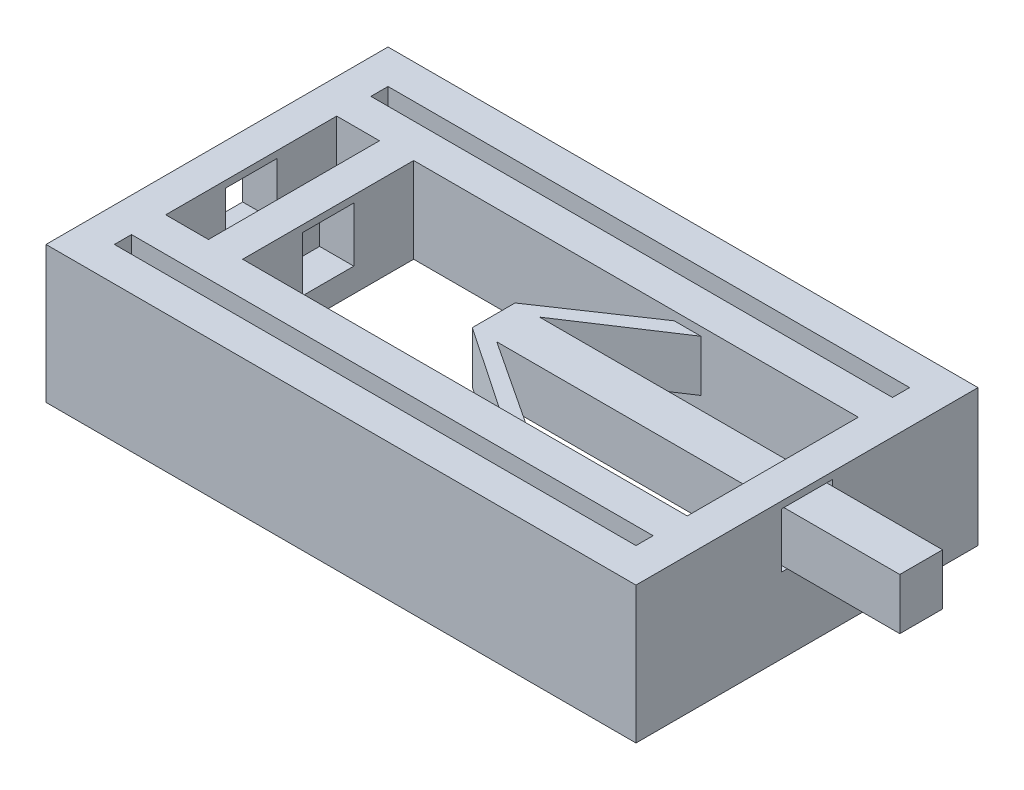
SolidWorks part; units mm, degrees
ref_plane "Ebene vorne" through (0, 0, 0) normal (0, 0, 1) x (1, 0, 0)
ref_plane "Ebene oben" through (0, 0, 0) normal (0, 1, 0) x (1, 0, 0)
ref_plane "Ebene rechts" through (0, 0, 0) normal (1, 0, 0) x (0, 0, -1)
sketch "Sketch2" plane through (0, 0, 0) normal (0, 1, 0) x (1, 0, 0)
  line L0 (-17.25, -7) -> (-17.25, 7)
  line L1 (-15.25, -5) -> (-12.75, -5)
  line L2 (-15.25, -5) -> (-15.25, 5)
  line L3 (-15.25, 5) -> (-12.75, 5)
  line L4 (15.25, -5) -> (15.25, 5)
  line L5 (-15.25, -5) -> (15.25, 5) construction
  line L6 (-15.25, 5) -> (15.25, -5) construction
  line L7 (-17.25, 7) -> (17.25, 7)
  line L8 (17.25, -7) -> (17.25, 7)
  line L9 (-17.25, -7) -> (17.25, -7)
  line L10 (-12.75, 5) -> (-12.75, -5)
  line L11 (-10.75, 5) -> (-10.75, -5)
  line L12 (-10.75, 5) -> (15.25, 5)
  line L13 (-10.75, -5) -> (15.25, -5)
  line L14 (-15.25, 5) -> (15.25, 5) construction
  line L16 (-15.25, -5) -> (15.25, -5) construction
  point P0 (0, 0)
  dimension "D1" = 10
  dimension "D2" = 30.5
  dimension "D4" = 2
  dimension "D5" = 2.5
  dimension "D3" = 2
extrude "Boss-Extrude2" add sketch "Sketch2" along normal blind 3.5 and the other way blind 1.5
sketch "Sketch9" plane through (0, 0, 0) normal (0, 1, 0) x (1, 0, 0)
  line L0 (-15.25, 8) -> (15.25, 8)
  line L5 (17.25, -10) -> (17.25, 8)
  line L6 (15.25, -8) -> (-15.25, -8)
  line L7 (15.25, -8) -> (15.25, 8)
  line L8 (15.25, 8) -> (-15.25, 8)
  line L9 (-15.25, -8) -> (-15.25, 8)
  line L10 (15.25, -8) -> (-15.25, 8) construction
  line L11 (15.25, 8) -> (-15.25, -8) construction
  line L12 (17.25, -10) -> (-17.25, -10)
  line L13 (-17.25, -10) -> (-17.25, 8)
  line L14 (-15.25, 10) -> (15.25, 10)
  line L15 (-17.25, 8) -> (-17.25, 10)
  line L16 (-15.25, 10) -> (-17.25, 10)
  line L17 (15.25, 10) -> (17.25, 10)
  line L18 (17.25, 8) -> (17.25, 10)
  point P0 (0, 0)
  point P1 (0, 0)
  dimension "D1" = 2
  dimension "D2" = 8
  dimension "D3" = 30.5
extrude "Boss-Extrude5" add sketch "Sketch9" along normal blind 3.5 and the other way blind 4.5 contours L5 L18 L17 L14 L16 L15 L13 L12 L6 L9 L0 L7
sketch "Sketch3" plane through (17.25, 0, 0) normal (1, 0, 0) x (0, 0, -1)
  line L0 (-1.5, 0) -> (-1.5, 3.1)
  line L1 (-1.5, 3.1) -> (1.5, 3.1)
  line L2 (1.5, 3.1) -> (1.5, 0)
  line L4 (-1.5, -0.1) -> (1.5, -0.1)
  line L5 (1.5, -0.1) -> (1.5, 0)
  line L6 (-1.5, -0.1) -> (-1.5, 0)
  line L7 (-1.5, 0) -> (1.5, 0) construction
  point P2 (0, 0)
  dimension "D1" = 3
  dimension "D2" = 3.1
  dimension "D3" = 0.1
  dimension "D4" = 0
extrude "Cut-Extrude1" cut sketch "Sketch3" against normal blind 2
sketch "Sketch4" plane through (-17.25, 0, 0) normal (-1, 0, 0) x (0, 0, 1)
  line L0 (-1.5, -0.1) -> (1.5, -0.1)
  line L1 (-1.5, 3.1) -> (1.5, 3.1)
  line L2 (-1.5, 3.1) -> (-1.5, 0)
  line L4 (1.5, 3.1) -> (1.5, 0)
  line L5 (1.5, -0.1) -> (1.5, 0)
  line L6 (-1.5, -0.1) -> (-1.5, 0)
  line L7 (-1.5, 0) -> (1.5, 0) construction
  line L8 (10, -4.5) -> (-10, -4.5) construction
  line L9 (-10, 3.5) -> (10, 3.5) construction
  line L10 (0, 3.1) -> (0, -0.1) construction
  point P4 (0, 0)
  point P14 (0, 1.5)
  dimension "D1" = 3
  dimension "D2" = 3.1
  dimension "D3" = 0.1
  dimension "D4" = 0
  dimension "D5" = 4.5
  dimension "D6" = 8
  dimension "D7" = 0.4
  dimension "D8" = 2
  dimension "D9" = 6
extrude "Cut-Extrude2" cut sketch "Sketch4" against normal blind 8
sketch "Sketch1" plane through (0, 0, 0) normal (0, 1, 0) x (1, 0, 0)
  line L0 (-1.073, -1.25) -> (4.4866, -5)
  line L2 (-1.073, 1.25) -> (-1.073, -1.25)
  line L3 (-0.3577, -1.25) -> (0.3577, -1.25) construction
  line L4 (23.927, 1.25) -> (23.927, -1.25)
  line L5 (0, 0) -> (23.927, 0) construction
  line L6 (-0.3577, -1.25) -> (5.2019, -5) construction
  line L11 (1.073, -1.25) -> (23.927, -1.25)
  line L15 (-1.073, 1.25) -> (4.4866, 5)
  line L18 (1.073, 1.25) -> (23.927, 1.25)
  line L19 (0, 1.25) -> (0, -1.25) construction
  line L21 (4.4866, 5) -> (4.4866, 6)
  line L22 (4.4866, 6) -> (6.0491, 6)
  line L24 (6.0491, 5) -> (6.0491, 6)
  line L26 (4.4866, -5) -> (4.4866, -6)
  line L27 (4.4866, -6) -> (6.0491, -6)
  line L29 (0.3577, -1.25) -> (5.9173, -5) [skipped]
  line L31 (0.3577, -1.25) -> (6.0491, -5)
  line L32 (-10.75, -5) -> (15.25, -5) construction
  line L33 (6.0491, -5) -> (6.0491, -6)
  line L34 (0.3577, -1.25) -> (1.073, -1.25)
  line L35 (0.3577, 1.25) -> (6.0491, 5)
  line L36 (1.073, -1.25) -> (6.6326, -5) [skipped]
  line L37 (0.3577, 1.25) -> (1.073, 1.25)
  point P24 (0, 0)
  dimension "D1" = 2.5
  dimension "D2" = 25
  dimension "D4" = 34
  dimension "D5" = 5
  dimension "D7" = 0.4
  dimension "D8" = 1
  dimension "D9" = 1
  dimension "D6" = 4
extrude "Boss-Extrude4" add sketch "Sketch1" along normal blind 3
sketch "Sketch5" plane through (0, 0, 0) normal (0, -1, 0) x (1, 0, 0)
  line L0 (0, 0.5) -> (0, -0.5)
  line L3 (0, 0.5) -> (7, 0.5)
  line L4 (7, 0.5) -> (7, -0.5)
  line L5 (7, -0.5) -> (0, -0.5)
  dimension "D1" = 7
  dimension "D2" = 0.5
  dimension "D3" = 0.5
extrude "Cut-Extrude3" cut sketch "Sketch5" against normal blind 1
sketch "Sketch6" plane through (0, 0, 0) normal (0, 1, 0) x (1, 0, 0)
  line L0 (7, 0.5) -> (7, -0.5) construction
  line L1 (3.5, 0) -> (3.5, 5.6889) construction
  line L3 (0, 0) -> (7, 0) construction
  dimension "D1" = 0
sketch "Sketch7" plane through (0, 0, 0) normal (0, 0, 1) x (1, 0, 0)
  line L0 (3.5, 0) -> (3.5, -1.2) construction
  line L1 (0, 0) -> (7, 0) construction
  circle A0 centre (3.5, -1.2) radius 0.2
  dimension "D2" = 0.4
  dimension "D1" = 1.2
extrude "Cut-Extrude4" cut sketch "Sketch7" against normal blind 6 and the other way blind 6
